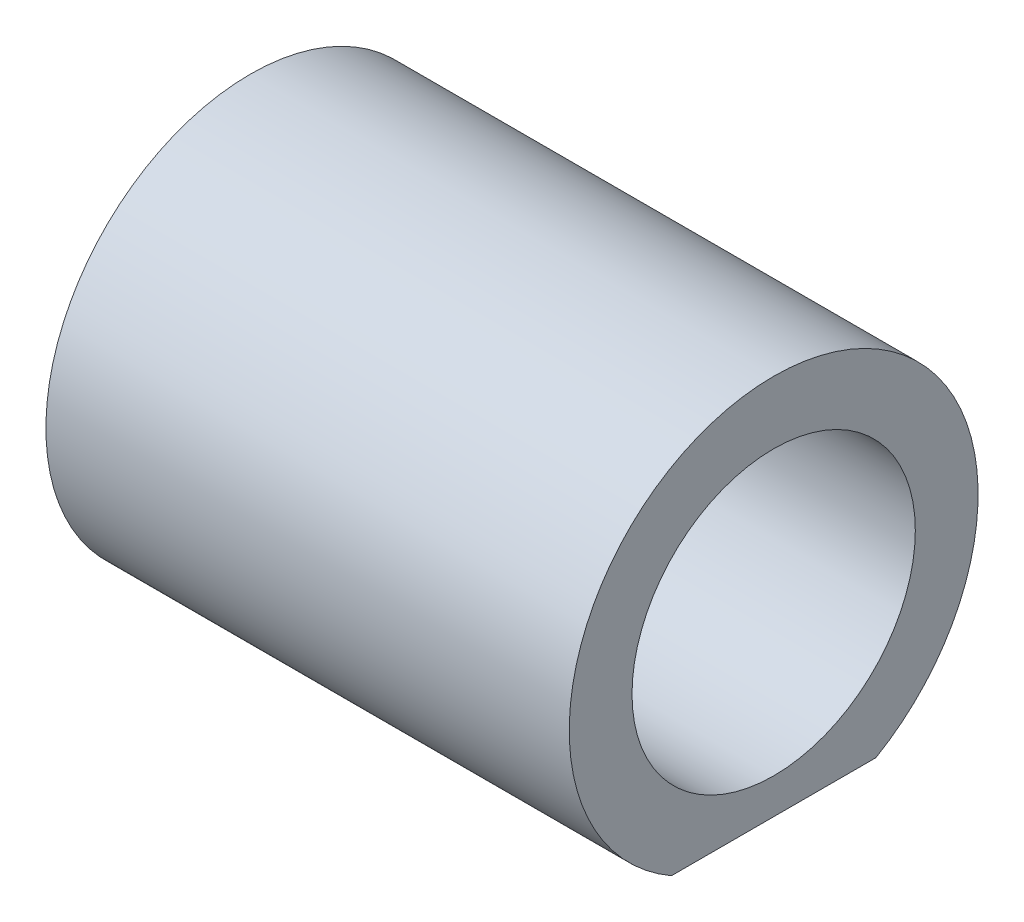
SolidWorks part; units mm, degrees
material "6061-T6 (SS)"
ref_plane "Front Plane" through (0, 0, 0) normal (1, 0, 0) x (0, 1, 0)
ref_plane "Top Plane" through (0, 0, 0) normal (0, 0, 1) x (0, 1, 0)
ref_plane "Right Plane" through (0, 0, 0) normal (0, 1, 0) x (-1, 0, 0)
sketch "Sketch1" plane through (0, 0, 0) normal (1, 0, 0) x (0, 1, 0)
  line L0 (-6.8741, -3.9688) -> (-6.8741, 3.9688)
  circle A0 centre (0, 0) radius 5.5
  arc A2 (-6.8741, 3.9688) -> (-6.8741, -3.9688) centre (0, 0) cw
  dimension "D2" = 11
  dimension "D1" = 7.9375
  dimension "D3" = 6.8741
extrude "Boss-Extrude1" add sketch "Sketch1" along normal blind 20.32
equation "\"D2@Sketch1\"=11mm"
equation "\"D3@Sketch1\"=0.5*0.625*cos(30)"
